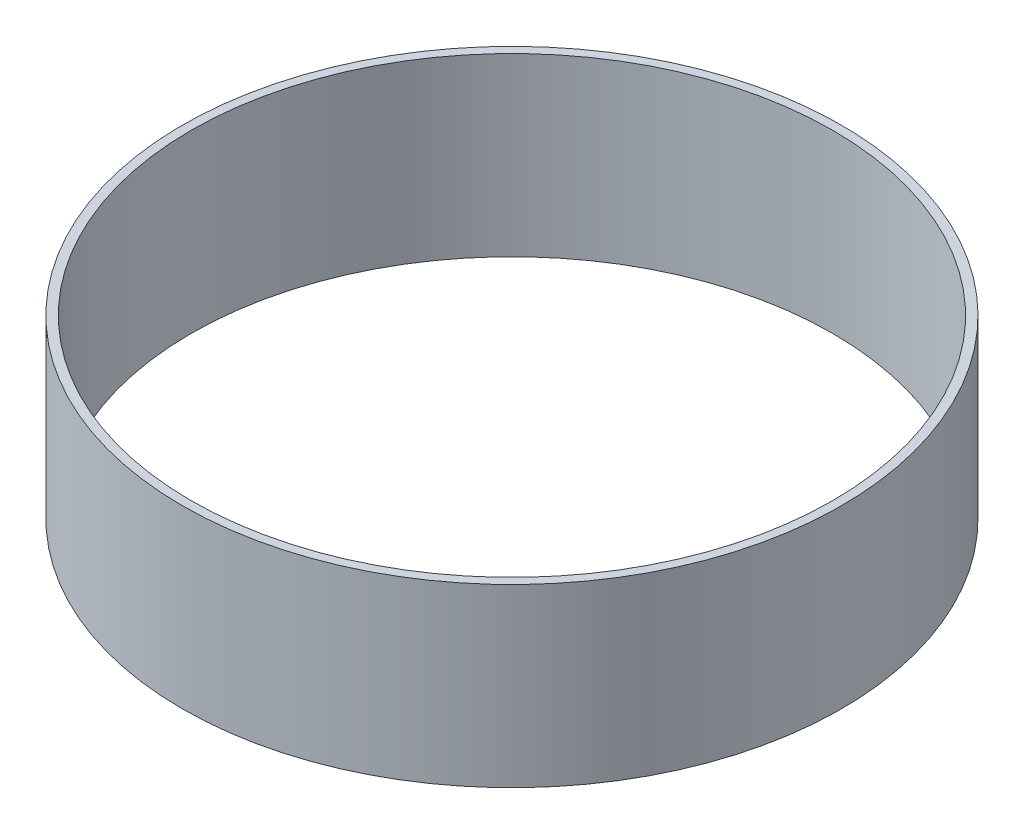
SolidWorks part; units mm, degrees
material "Thornel P30"
ref_plane "Front Plane" through (0, 0, 0) normal (0, 0, 1) x (1, 0, 0)
ref_plane "Top Plane" through (0, 0, 0) normal (0, 1, 0) x (1, 0, 0)
ref_plane "Right Plane" through (0, 0, 0) normal (1, 0, 0) x (0, 0, -1)
sketch "Sketch1" plane through (0, 0, 0) normal (0, 0, 1) x (1, 0, 0)
  line L0 (0, 0) -> (0, -104.8247) construction
  line L1 (138.9062, 192.9517) -> (142.7163, 192.9517)
  line L2 (138.9062, 192.9517) -> (138.9062, 116.7517)
  line L3 (138.9062, 116.7517) -> (142.7163, 116.7517)
  line L4 (142.7163, 192.9517) -> (142.7163, 116.7517)
  line L5 (0, -164.1944) -> (0, 164.1944)
  point P10 (0, 0)
  dimension "D1" = 142.7163
  dimension "D2" = 3.81
  dimension "D3" = 76.2
revolve "Revolve1" add sketch "Sketch1" angle 360 about L0
sketch "Sketch2" plane through (0, 0, 0) normal (1, 0, 0) x (0, 0, -1)
  line L0 (-142.7163, 116.7517) -> (142.7163, 116.7517) construction
  line L1 (-0.762, 180.2517) -> (0.762, 180.2517)
  line L2 (-0.762, 180.2517) -> (-0.762, 129.4517)
  line L3 (-0.762, 129.4517) -> (0.762, 129.4517)
  line L4 (0.762, 180.2517) -> (0.762, 129.4517)
  line L5 (142.7163, 192.9517) -> (-142.7163, 192.9517) construction
  point P8 (0, 180.2517)
  dimension "D1" = 1.524
  dimension "D2" = 12.7
  dimension "D3" = 12.7
